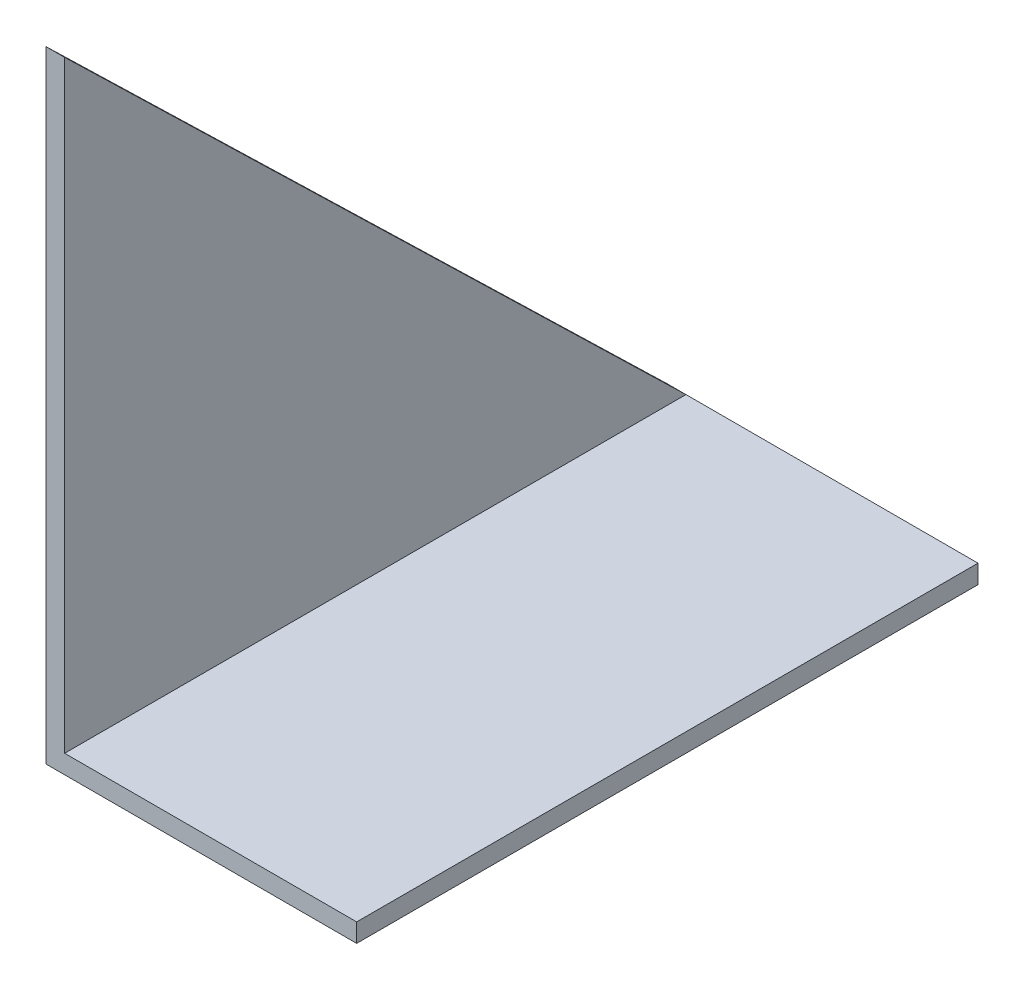
SolidWorks part; units mm, degrees
ref_plane "Alzado" through (0, 0, 0) normal (0, 0, 1) x (1, 0, 0)
ref_plane "Planta" through (0, 0, 0) normal (0, 1, 0) x (1, 0, 0)
ref_plane "Vista lateral" through (0, 0, 0) normal (1, 0, 0) x (0, 0, -1)
sketch "Croquis1" plane through (0, 0, 0) normal (0, 0, 1) x (1, 0, 0)
  line L1 (1.5, -50) -> (-1.5, -50)
  line L2 (1.5, -50) -> (1.5, 50)
  line L3 (1.5, 50) -> (-1.5, 50)
  line L4 (-1.5, -50) -> (-1.5, 50)
  line L5 (1.5, -50) -> (-1.5, 50) construction
  line L6 (1.5, 50) -> (-1.5, -50) construction
  line L7 (1.5, -50) -> (48.5, -50)
  line L8 (1.5, -50) -> (1.5, -47)
  line L9 (1.5, -47) -> (48.5, -47)
  line L10 (48.5, -50) -> (48.5, -47)
  point P0 (0, 0)
  point P9 (48.5, -48.5)
  dimension "D1" = 100
  dimension "D2" = 50
  dimension "D3" = 3
  dimension "D4" = 3
extrude "Saliente-Extruir1" add sketch "Croquis1" along normal mid plane 100 contours L4 L1 L2 L3 | L7 L10 L9 L8
sketch "Croquis2" plane through (1.5, 0, 0) normal (1, 0, 0) x (0, 0, -1)
  line L0 (-50, 50) -> (50, -47)
  line L4 (-50, 50) -> (-50, -47)
  line L5 (-50, -47) -> (50, -47)
  line L6 (50, -47) -> (50, 50)
  line L7 (50, 50) -> (-50, 50)
  line L8 (-50, 50) -> (-50, -47)
  line L9 (-50, -47) -> (50, -47)
  line L10 (50, -47) -> (50, 50)
  line L11 (50, 50) -> (-50, 50)
  line M7 (50, -47) -> (50, 50)
  line M8 (50, 50) -> (-50, 50)
  dimension "D1" = 0
extrude "Cortar-Extruir1" cut sketch "Croquis2" against normal blind 100 contours L0 M8 M7
